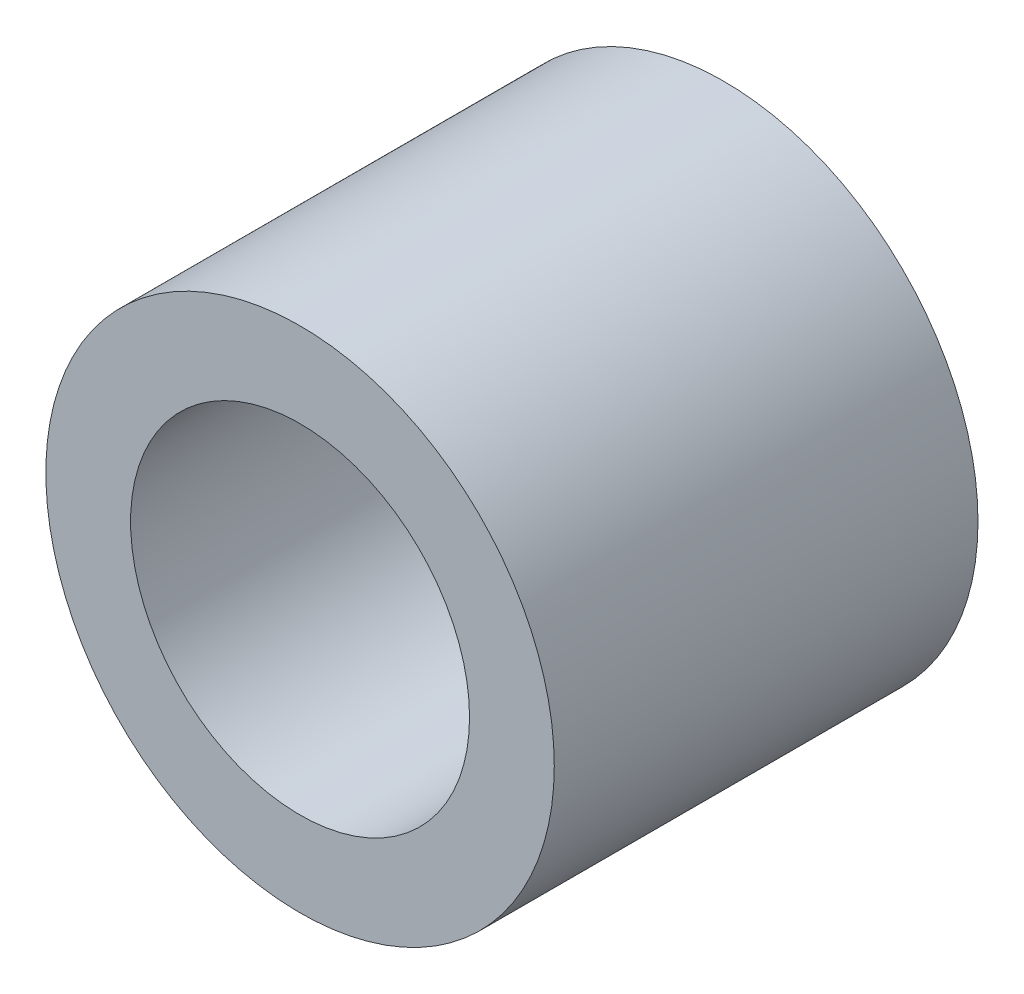
SolidWorks part; units mm, degrees
ref_plane "Front Plane" through (0, 0, 0) normal (0, 0, 1) x (1, 0, 0)
ref_plane "Top Plane" through (0, 0, 0) normal (0, 1, 0) x (1, 0, 0)
ref_plane "Right Plane" through (0, 0, 0) normal (1, 0, 0) x (0, 0, -1)
sketch "Sketch1" plane through (0, 0, 0) normal (0, 0, 1) x (1, 0, 0)
  circle A0 centre (0, 0) radius 300
  circle A1 centre (0, 0) radius 200
  dimension "D1" = 600
  dimension "D2" = 100
extrude "Boss-Extrude2" add sketch "Sketch1" along normal blind 500
